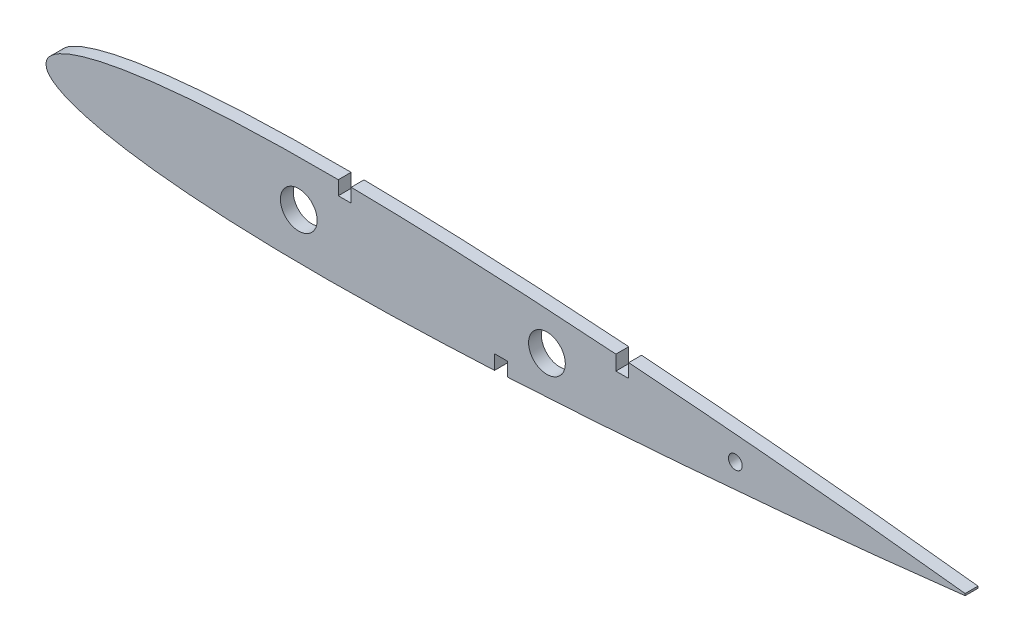
SolidWorks part; units mm, degrees
material "Фанера"
ref_plane "Спереди" through (0, 0, 0) normal (0, 0, 1) x (1, 0, 0)
ref_plane "Сверху" through (0, 0, 0) normal (0, 1, 0) x (1, 0, 0)
ref_plane "Справа" through (0, 0, 0) normal (1, 0, 0) x (0, 0, -1)
curve "Кривая1"
  spline degree 3 poles (200, 0.21, 0) (199.5201, 0.266, 0) (198.1795, 0.4223, 0) (195.7476, 0.7017, 0) (192.5308, 1.0651, 0) (188.7716, 1.4807, 0) (184.587, 1.9325, 0) (180.0562, 2.4092, 0) (175.2384, 2.9026, 0) (170.1814, 3.4057, 0) (164.925, 3.9132, 0) (159.5032, 4.4204, 0) (153.9461, 4.9234, 0) (148.2803, 5.4186, 0) (142.5299, 5.9028, 0) (136.7168, 6.3729, 0) (130.8615, 6.8262, 0) (124.9826, 7.2598, 0) (119.0976, 7.6711, 0) (113.2231, 8.0575, 0) (107.3746, 8.4163, 0) (101.5666, 8.7448, 0) (95.8133, 9.0407, 0) (90.1279, 9.3014, 0) (84.5231, 9.5247, 0) (79.0111, 9.7082, 0) (73.6037, 9.85, 0) (68.3121, 9.9482, 0) (63.1472, 10.0012, 0) (58.1196, 10.0077, 0) (53.2393, 9.9665, 0) (48.5164, 9.8771, 0) (43.9603, 9.7388, 0) (39.5803, 9.5517, 0) (35.3856, 9.3161, 0) (31.3849, 9.0325, 0) (27.5868, 8.7017, 0) (23.9997, 8.3252, 0) (20.6317, 7.9043, 0) (17.4909, 7.4408, 0) (14.5849, 6.9366, 0) (11.9213, 6.3939, 0) (9.5074, 5.8148, 0) (7.3502, 5.2016, 0) (5.4564, 4.5565, 0) (3.8315, 3.8815, 0) (2.4822, 3.178, 0) (1.4075, 2.4454, 0) (0.6238, 1.6789, 0) (0.1006, 0.8638, 0) (0.0324, 0.2785, 0) (0, 0, 0) knots 0 0 0 0 0.007145 0.019956 0.036196 0.055011 0.075879 0.098429 0.122376 0.147488 0.173572 0.20046 0.228005 0.256076 0.284555 0.313333 0.34231 0.371393 0.400496 0.429538 0.458442 0.487136 0.515552 0.543624 0.57129 0.598491 0.62517 0.651272 0.676746 0.701542 0.725611 0.748908 0.771388 0.793008 0.813728 0.833508 0.85231 0.870097 0.886836 0.902493 0.917037 0.930441 0.94268 0.953734 0.96359 0.972247 0.979722 0.986065 0.991385 0.995901 1 1 1 1
curve "Кривая2"
  spline degree 3 poles (0, 0, 0) (0.0324, -0.2785, 0) (0.1006, -0.8638, 0) (0.6238, -1.6789, 0) (1.4075, -2.4454, 0) (2.4822, -3.178, 0) (3.8315, -3.8815, 0) (5.4564, -4.5565, 0) (7.3502, -5.2016, 0) (9.5074, -5.8148, 0) (11.9213, -6.3939, 0) (14.5849, -6.9366, 0) (17.4909, -7.4408, 0) (20.6317, -7.9043, 0) (23.9997, -8.3252, 0) (27.5868, -8.7017, 0) (31.3849, -9.0325, 0) (35.3856, -9.3161, 0) (39.5803, -9.5517, 0) (43.9603, -9.7388, 0) (48.5164, -9.8771, 0) (53.2393, -9.9665, 0) (58.1196, -10.0077, 0) (63.1472, -10.0012, 0) (68.3121, -9.9482, 0) (73.6037, -9.85, 0) (79.0111, -9.7082, 0) (84.5231, -9.5247, 0) (90.1279, -9.3014, 0) (95.8133, -9.0407, 0) (101.5666, -8.7448, 0) (107.3746, -8.4163, 0) (113.2231, -8.0575, 0) (119.0976, -7.6711, 0) (124.9826, -7.2598, 0) (130.8615, -6.8262, 0) (136.7168, -6.3729, 0) (142.5299, -5.9028, 0) (148.2803, -5.4186, 0) (153.9461, -4.9234, 0) (159.5032, -4.4204, 0) (164.925, -3.9132, 0) (170.1814, -3.4057, 0) (175.2384, -2.9026, 0) (180.0562, -2.4092, 0) (184.587, -1.9325, 0) (188.7716, -1.4807, 0) (192.5308, -1.0651, 0) (195.7476, -0.7017, 0) (198.1795, -0.4223, 0) (199.5201, -0.266, 0) (200, -0.21, 0) knots 0 0 0 0 0.004099 0.008615 0.013935 0.020278 0.027753 0.03641 0.046266 0.05732 0.069559 0.082963 0.097507 0.113164 0.129903 0.14769 0.166492 0.186272 0.206992 0.228612 0.251092 0.274389 0.298458 0.323254 0.348728 0.37483 0.401509 0.42871 0.456376 0.484448 0.512864 0.541558 0.570462 0.599504 0.628607 0.65769 0.686667 0.715445 0.743924 0.771995 0.79954 0.826428 0.852512 0.877624 0.901571 0.924121 0.944989 0.963804 0.980044 0.992855 1 1 1 1
sketch "Эскиз3" plane through (0, 0, 0) normal (0, 0, 1) x (1, 0, 0)
  line L0 (200, 0.21) -> (200, -0.21)
  line L1 (63.6, 9.9908) -> (63.6, 6.9656)
  line L2 (63.6, 6.9656) -> (66.4, 6.9656)
  line L3 (66.4, 6.9656) -> (66.4, 9.9656)
  line L4 (97.6, -8.9469) -> (97.6, -5.8023)
  line L5 (97.6, -5.8023) -> (100.4, -5.8023)
  line L6 (100.4, -5.8023) -> (100.4, -8.8023)
  line L7 (124, 7.3263) -> (124, 4.1244)
  line L8 (124, 4.1244) -> (126.8, 4.1244)
  line L9 (126.8, 4.1244) -> (126.8, 7.1244)
  circle A0 centre (109, 0) radius 4
  circle A1 centre (55, 0) radius 4
  arc A2 (150, 5.2672) -> (150, -5.2672) centre (150, 0) ccw
  arc A3 (142.8327, 5.8745) -> (142.8327, -5.8745) centre (150, 0) ccw
  circle A4 centre (150, 0) radius 1.5
  spline S0 degree 3 poles (-12387.2221, -3898.3721) (203.0614, 99.0345) (-9.108, 13.4836) (0.6238, -1.6789) (1.4075, -2.4454) (2.4822, -3.178) (3.8315, -3.8815) (5.4564, -4.5565) (7.3502, -5.2016) (9.5074, -5.8148) (11.9213, -6.3939) (14.5849, -6.9366) (17.4909, -7.4408) (20.6317, -7.9043) (23.9997, -8.3252) (27.5868, -8.7017) (31.3849, -9.0325) (35.3856, -9.3161) (39.5803, -9.5517) (43.9603, -9.7388) (48.5164, -9.8771) (53.2393, -9.9665) (58.1196, -10.0077) (63.1472, -10.0012) (68.3121, -9.9482) (73.6037, -9.85) (79.0111, -9.7082) (84.5231, -9.5247) (90.1279, -9.3014) (95.8133, -9.0407) (101.5666, -8.7448) (107.3746, -8.4163) (113.2231, -8.0575) (119.0976, -7.6711) (124.9826, -7.2598) (130.8615, -6.8262) (136.7168, -6.3729) (142.5299, -5.9028) (148.2803, -5.4186) (153.9461, -4.9234) (161.2601, -4.2614) (168.3719, -3.5857) (175.2384, -2.9026) (180.0562, -2.4092) (184.587, -1.9325) (188.7716, -1.4807) (192.5308, -1.0651) (195.7476, -0.7017) (367.2459, 19.0002) (533.3374, 75.742) (2203.2181, -12825.1076) knots -0.245281 -0.245281 -0.245281 -0.245281 0.004099 0.008615 0.013935 0.020278 0.027753 0.03641 0.046266 0.05732 0.069559 0.082963 0.097507 0.113164 0.129903 0.14769 0.166492 0.186272 0.206992 0.228612 0.251092 0.274389 0.298458 0.323254 0.348728 0.37483 0.401509 0.42871 0.456376 0.484448 0.512864 0.541558 0.570462 0.599504 0.628607 0.65769 0.686667 0.715445 0.743924 0.771995 0.79954 0.852512 0.877624 0.901571 0.924121 0.944989 0.963804 0.980044 0.992855 3.516294 3.516294 3.516294 3.516294 only from (0, 0) to (200, -0.21) construction
  spline S1 degree 3 poles (2963.6132, 18775.4593) (577.7793, -91.6187) (390.084, -21.6238) (195.7476, 0.7017) (192.5308, 1.0651) (188.7716, 1.4807) (184.587, 1.9325) (180.0562, 2.4092) (175.2384, 2.9026) (168.3719, 3.5857) (161.2601, 4.2614) (153.9461, 4.9234) (148.2803, 5.4186) (142.5299, 5.9028) (136.7168, 6.3729) (130.8615, 6.8262) (124.9826, 7.2598) (119.0976, 7.6711) (113.2231, 8.0575) (107.3746, 8.4163) (101.5666, 8.7448) (95.8133, 9.0407) (90.1279, 9.3014) (84.5231, 9.5247) (79.0111, 9.7082) (73.6037, 9.85) (68.3121, 9.9482) (63.1472, 10.0012) (58.1196, 10.0077) (53.2393, 9.9665) (48.5164, 9.8771) (43.9603, 9.7388) (39.5803, 9.5517) (35.3856, 9.3161) (31.3849, 9.0325) (27.5868, 8.7017) (23.9997, 8.3252) (20.6317, 7.9043) (17.4909, 7.4408) (14.5849, 6.9366) (11.9213, 6.3939) (9.5074, 5.8148) (7.3502, 5.2016) (5.4564, 4.5565) (3.8315, 3.8815) (2.4822, 3.178) (1.4075, 2.4454) (0.6238, 1.6789) (-10.3471, -15.4142) (261.9688, -122.4712) (-18088.7696, 5709.5905) knots -2.856205 -2.856205 -2.856205 -2.856205 0.007145 0.019956 0.036196 0.055011 0.075879 0.098429 0.122376 0.147488 0.20046 0.228005 0.256076 0.284555 0.313333 0.34231 0.371393 0.400496 0.429538 0.458442 0.487136 0.515552 0.543624 0.57129 0.598491 0.62517 0.651272 0.676746 0.701542 0.725611 0.748908 0.771388 0.793008 0.813728 0.833508 0.85231 0.870097 0.886836 0.902493 0.917037 0.930441 0.94268 0.953734 0.96359 0.972247 0.979722 0.986065 0.991385 0.995901 1.278285 1.278285 1.278285 1.278285 only from (200, 0.21) to (0, 0) construction
  spline S2 degree 3 poles (0, 0) (0.0324, -0.2785) (0.1006, -0.8638) (0.6238, -1.6789) (1.4075, -2.4454) (2.4822, -3.178) (3.8315, -3.8815) (5.4564, -4.5565) (7.3502, -5.2016) (9.5074, -5.8148) (11.9213, -6.3939) (14.5849, -6.9366) (17.4909, -7.4408) (20.6317, -7.9043) (23.9997, -8.3252) (27.5868, -8.7017) (31.3849, -9.0325) (35.3856, -9.3161) (39.5803, -9.5517) (43.9603, -9.7388) (48.5164, -9.8771) (53.2393, -9.9665) (58.1196, -10.0077) (63.1472, -10.0012) (68.3121, -9.9482) (73.6037, -9.85) (79.0111, -9.7082) (84.5231, -9.5247) (90.1279, -9.3014) (94.497, -9.1011) (96.9966, -8.9773) (97.6, -8.9469) knots 0 0 0 0 0.004099 0.008615 0.013935 0.020278 0.027753 0.03641 0.046266 0.05732 0.069559 0.082963 0.097507 0.113164 0.129903 0.14769 0.166492 0.186272 0.206992 0.228612 0.251092 0.274389 0.298458 0.323254 0.348728 0.37483 0.401509 0.42871 0.456376 0.484448 0.493381 0.493381 0.493381 0.493381
  spline S3 degree 3 poles (200, 0.21) (199.5201, 0.266) (198.1795, 0.4223) (195.7476, 0.7017) (192.5308, 1.0651) (188.7716, 1.4807) (184.587, 1.9325) (180.0562, 2.4092) (175.2384, 2.9026) (168.3719, 3.5857) (161.2601, 4.2614) (153.9461, 4.9234) (148.2803, 5.4186) (142.5299, 5.9028) (136.7168, 6.3729) (131.4667, 6.7793) (128.1563, 7.0254) (126.8, 7.1244) knots 0 0 0 0 0.007145 0.019956 0.036196 0.055011 0.075879 0.098429 0.122376 0.147488 0.20046 0.228005 0.256076 0.284555 0.313333 0.34231 0.362417 0.362417 0.362417 0.362417
  spline S4 degree 3 poles (63.6, 9.9908) (63.4338, 9.9918) (61.5906, 10.0032) (58.1196, 10.0077) (53.2393, 9.9665) (48.5164, 9.8771) (43.9603, 9.7388) (39.5803, 9.5517) (35.3856, 9.3161) (31.3849, 9.0325) (27.5868, 8.7017) (23.9997, 8.3252) (20.6317, 7.9043) (17.4909, 7.4408) (14.5849, 6.9366) (11.9213, 6.3939) (9.5074, 5.8148) (7.3502, 5.2016) (5.4564, 4.5565) (3.8315, 3.8815) (2.4822, 3.178) (1.4075, 2.4454) (0.6238, 1.6789) (0.1006, 0.8638) (0.0324, 0.2785) (0, 0) knots 0.674288 0.674288 0.674288 0.674288 0.676746 0.701542 0.725611 0.748908 0.771388 0.793008 0.813728 0.833508 0.85231 0.870097 0.886836 0.902493 0.917037 0.930441 0.94268 0.953734 0.96359 0.972247 0.979722 0.986065 0.991385 0.995901 1 1 1 1
  spline S5 degree 3 poles (100.4, -8.8023) (100.7825, -8.782) (103.1029, -8.6579) (107.3746, -8.4163) (113.2231, -8.0575) (119.0976, -7.6711) (124.9826, -7.2598) (130.8615, -6.8262) (136.7168, -6.3729) (142.5299, -5.9028) (148.2803, -5.4186) (153.9461, -4.9234) (161.2601, -4.2614) (168.3719, -3.5857) (175.2384, -2.9026) (180.0562, -2.4092) (184.587, -1.9325) (188.7716, -1.4807) (192.5308, -1.0651) (195.7476, -0.7017) (198.1795, -0.4223) (199.5201, -0.266) (200, -0.21) knots 0.5072 0.5072 0.5072 0.5072 0.512864 0.541558 0.570462 0.599504 0.628607 0.65769 0.686667 0.715445 0.743924 0.771995 0.79954 0.852512 0.877624 0.901571 0.924121 0.944989 0.963804 0.980044 0.992855 1 1 1 1
  spline S6 degree 3 poles (124, 7.3263) (122.3646, 7.4427) (118.7696, 7.6927) (113.2231, 8.0575) (107.3746, 8.4163) (101.5666, 8.7448) (95.8133, 9.0407) (90.1279, 9.3014) (84.5231, 9.5247) (79.0111, 9.7082) (73.6037, 9.85) (69.4115, 9.9278) (67.0232, 9.9585) (66.4, 9.9656) knots 0.376253 0.376253 0.376253 0.376253 0.400496 0.429538 0.458442 0.487136 0.515552 0.543624 0.57129 0.598491 0.62517 0.651272 0.660487 0.660487 0.660487 0.660487
  point P17 (65, 6.9656)
  point P20 (99, -5.8023)
  dimension "D1" = 8
  dimension "D2" = 8
  dimension "D16" = 5.2672
  dimension "D17" = 9.2672
  dimension "D18" = 3
  dimension "D3" = 109
  dimension "D4" = 55
  dimension "D5" = 2.8
  dimension "D6" = 2.8
  dimension "D7" = 2.8
  dimension "D8" = 10
  dimension "D9" = 10
  dimension "D10" = 15
  dimension "D11" = 3
  dimension "D12" = 3
  dimension "D13" = 3
  dimension "D14" = 150
  dimension "D15" = 10.5344
extrude "Бобышка-Вытянуть1" add sketch "Эскиз3" along normal mid plane 2.8 contours L7 S6 L3 L2 L1 S4 S2 L4 L5 L6 S5 A3 S3 L9 L8 A0 A1 | A3 S5 A2 S3 | A2 S5 L0 S3 A4
equation "\"D16@Эскиз3\"=\"D15@Эскиз3\"/2"
equation "\"D17@Эскиз3\"=\"D16@Эскиз3\"+4"
